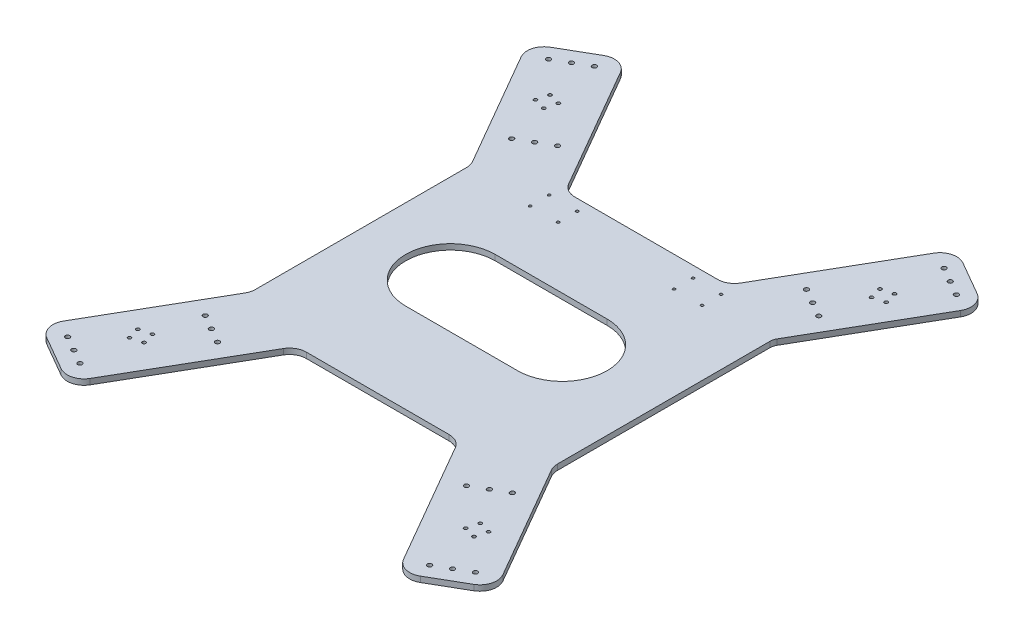
SolidWorks part; units mm, degrees
ref_plane "Front Plane" through (0, 0, 0) normal (0, 0, 1) x (1, 0, 0)
ref_plane "Top Plane" through (0, 0, 0) normal (0, 1, 0) x (1, 0, 0)
ref_plane "Right Plane" through (0, 0, 0) normal (1, 0, 0) x (0, 0, -1)
sketch "Sketch1" plane through (0, 0, 0) normal (0, 1, 0) x (1, 0, 0)
  line L0 (-171.45, 0) -> (171.45, 0) construction
  line L1 (-171.45, 0) -> (-258.7801, 151.2602)
  line L2 (-258.7801, 151.2602) -> (-187.2897, 192.5352)
  line L3 (-187.2897, 192.5352) -> (-92.0397, 27.5574)
  line L4 (-92.0397, 27.5574) -> (92.0397, 27.5574)
  line L5 (92.0397, 27.5574) -> (187.2897, 192.5352)
  line L6 (187.2897, 192.5352) -> (258.7801, 151.2602)
  line L7 (258.7801, 151.2602) -> (171.45, 0)
  line L8 (-92.0397, 27.5574) -> (-187.3603, 27.5574) construction
  line L9 (92.0397, 27.5574) -> (187.3603, 27.5574) construction
  line L10 (0, 27.5574) -> (0, -277.2426) construction
  line L11 (-171.45, -124.8426) -> (171.45, -124.8426) construction
  line L12 (258.7801, -400.9455) -> (171.45, -249.6852)
  line L13 (187.2897, -442.2205) -> (258.7801, -400.9455)
  line L14 (92.0397, -277.2426) -> (187.2897, -442.2205)
  line L15 (-92.0397, -277.2426) -> (92.0397, -277.2426)
  line L16 (-187.2897, -442.2205) -> (-92.0397, -277.2426)
  line L17 (-258.7801, -400.9455) -> (-187.2897, -442.2205)
  line L18 (-171.45, -249.6852) -> (-258.7801, -400.9455)
  line L19 (-171.45, -249.6852) -> (171.45, -249.6852) construction
  line L20 (-171.45, 0) -> (-171.45, -249.6852)
  line L21 (171.45, 0) -> (171.45, -249.6852)
  point P2 (-139.7, 27.5574)
  point P11 (139.7, 27.5574)
  point P17 (0, -124.8426)
  point P18 (0, -124.8426)
  dimension "D1" = 60
  dimension "D2" = 82.55
  dimension "D3" = 190.5
  dimension "D4" = 279.4
  dimension "D5" = 342.9
  dimension "D6" = 304.8
extrude "Boss-Extrude1" add sketch "Sketch1" along normal blind 6.35
fillet "Fillet1" radius 19.05 15 edges at (-258.7801, 3.175, -151.2602) (92.0397, 3.175, -27.5574) (-92.0397, 3.175, -27.5574) (187.2897, 3.175, -192.5352) (258.7801, 3.175, -151.2602) (-187.2897, 3.175, -192.5352) (171.45, 3.175, 249.6852) (258.7801, 3.175, 400.9455) (187.2897, 3.175, 442.2205) (92.0397, 3.175, 277.2426) (-171.45, 3.175, 249.6852) (-258.7801, 3.175, 400.9455) (-187.2897, 3.175, 442.2205) (-92.0397, 3.175, 277.2426) (-171.45, 3.175, 0)
sketch "Sketch2" plane through (0, 6.35, 0) normal (0, 1, 0) x (1, 0, 0)
  line L0 (-69.85, -77.8526) -> (57.15, -77.8526) construction
  line L1 (-69.85, -77.8526) -> (57.15, -77.8526) construction
  line L3 (-69.85, -171.8326) -> (57.15, -171.8326) construction
  line L4 (-69.85, -171.8326) -> (57.15, -171.8326) construction
  line L5 (-69.85, -74.0426) -> (57.15, -74.0426)
  line L6 (-69.85, -175.6426) -> (57.15, -175.6426)
  arc A0 (-69.85, -77.8526) -> (-69.85, -171.8326) centre (-69.85, -124.8426) ccw construction
  arc A1 (57.15, -171.8326) -> (57.15, -77.8526) centre (57.15, -124.8426) ccw construction
  arc A2 (-69.85, -77.8526) -> (-69.85, -171.8326) centre (-69.85, -124.8426) ccw construction
  arc A3 (57.15, -171.8326) -> (57.15, -77.8526) centre (57.15, -124.8426) ccw construction
  arc A4 (57.15, -175.6426) -> (57.15, -74.0426) centre (57.15, -124.8426) ccw
  arc A5 (-69.85, -74.0426) -> (-69.85, -175.6426) centre (-69.85, -124.8426) ccw
  dimension "D1" = 3.81
extrude "Cut-Extrude1" cut sketch "Sketch2" against normal through all
sketch "Sketch4" plane through (0, 0, 0) normal (0, -1, 0) x (1, 0, 0)
  line L0 (242.2823, -160.7852) -> (203.7875, -183.0102) construction
  line L1 (177.7647, -176.0374) -> (97.539, -37.0824) construction
  line L2 (150.4597, -128.7438) -> (221.9501, -87.4688) construction
  line L3 (171.45, 0) -> (249.2551, -134.7624) construction
  circle A0 centre (198.3921, -167.0611) radius 2.54
  circle A1 centre (214.8899, -157.5361) radius 2.54
  circle A2 centre (231.3877, -148.0111) radius 2.54
  circle A3 centre (141.2421, -68.0744) radius 2.54
  circle A4 centre (174.2377, -49.0244) radius 2.54
  circle A5 centre (157.7399, -58.5494) radius 2.54
  dimension "D4" = 5.08
  dimension "D1" = 16.51
  dimension "D2" = 22.352
  dimension "D5" = 57.15
  dimension "D3" = 3
extrude "Cut-Extrude2" cut sketch "Sketch4" against normal through all
ref_plane "Plane1" through (0, 0, 124.8426) normal (0, 0, -1) x (-1, 0, 0)
sketch "Sketch6" plane through (0, 6.35, 0) normal (0, 1, 0) x (1, 0, 0)
  line L0 (221.9501, 87.4688) -> (150.4597, 128.7438) construction
  line L1 (171.45, 0) -> (249.2551, 134.7624) construction
  line L2 (177.7647, 176.0374) -> (97.539, 37.0824) construction
  line L3 (242.2823, 160.7852) -> (203.7875, 183.0102) construction
  line L4 (195.4768, 113.7517) -> (185.9518, 97.2539) construction
  circle A0 centre (157.7399, 58.5494) radius 2.54 construction
  circle A1 centre (190.7143, 105.5028) radius 9.525 construction
  circle A2 centre (198.9632, 100.7403) radius 1.905
  circle A3 centre (185.9518, 97.2539) radius 1.905
  circle A4 centre (182.4654, 110.2653) radius 1.905
  circle A5 centre (195.4768, 113.7517) radius 1.905
  point P23 (190.7143, 105.5028)
  dimension "D1" = 57.15
  dimension "D2" = 19.05
  dimension "D4" = 3.81
  dimension "D3" = 36.068
  dimension "D5" = 4
extrude "Cut-Extrude3" cut sketch "Sketch6" against normal through all
mirror "Mirror1" about plane through (0, 0, 0) normal (1, 0, 0) of "Cut-Extrude2", "Cut-Extrude3"
mirror "Mirror2" about plane through (0, 0, 124.8426) normal (0, 0, -1) of "Cut-Extrude2", "Cut-Extrude1", "Mirror1", "Cut-Extrude3"
fillet "Fillet2" radius 12.7 1 edges at (171.45, 3.175, 0)
sketch "Sketch7" plane through (0, 6.35, 0) normal (0, 1, 0) x (1, 0, 0)
  line L0 (0, 0) -> (0, 27.5574) construction
  line L1 (81.0412, 27.5574) -> (-81.0412, 27.5574) construction
  line L2 (-97.539, 37.0824) -> (-97.539, 0) construction
  line L3 (-97.539, 0) -> (0, 0) construction
  line L4 (-97.539, 0) -> (-97.539, -6.7326) construction
  circle A0 centre (-97.539, 14.8574) radius 1.524
  circle A1 centre (-97.539, -6.7326) radius 1.524
  circle A2 centre (-65.789, 14.8574) radius 1.524
  circle A3 centre (-65.789, -6.7326) radius 1.524
  circle A4 centre (97.539, -6.7326) radius 1.524
  circle A5 centre (97.539, 14.8574) radius 1.524
  circle A6 centre (65.789, 14.8574) radius 1.524
  circle A7 centre (65.789, -6.7326) radius 1.524
  dimension "D2" = 3.048
  dimension "D3" = 21.59
  dimension "D5" = 31.75
  dimension "D1" = 12.7
  dimension "D4" = 2
extrude "Cut-Extrude4" cut sketch "Sketch7" against normal through all
